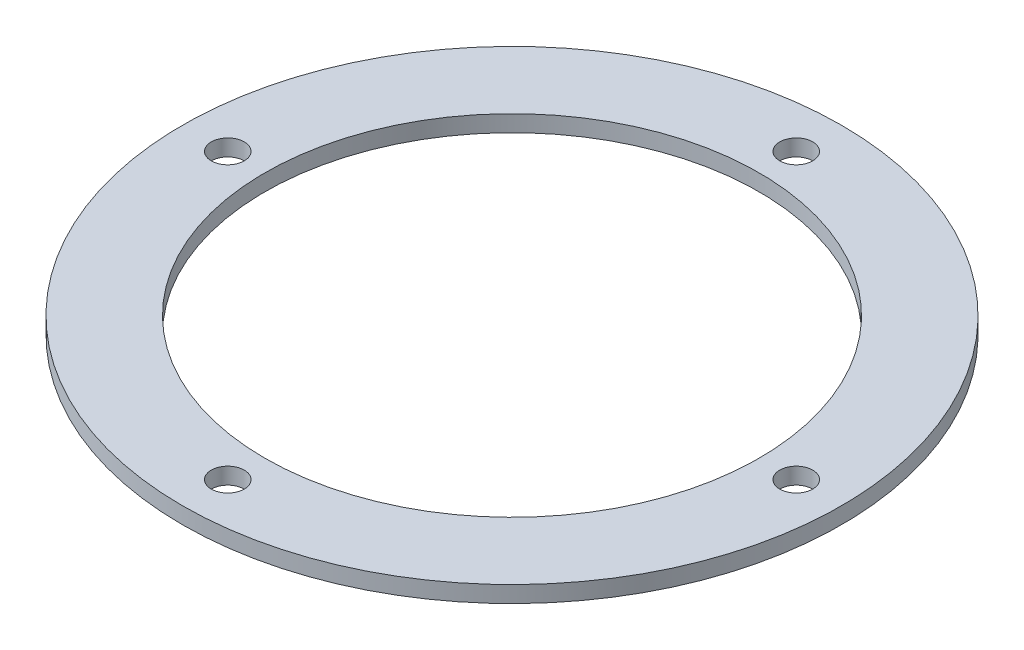
SolidWorks part; units mm, degrees
ref_plane "前视基准面" through (0, 0, 0) normal (0, 0, 1) x (1, 0, 0)
ref_plane "上视基准面" through (0, 0, 0) normal (0, 1, 0) x (1, 0, 0)
ref_plane "右视基准面" through (0, 0, 0) normal (1, 0, 0) x (0, 0, -1)
other "Configuration Table"
sketch "草图2" plane through (0, 0, 0) normal (0, 1, 0) x (1, 0, 0)
  circle A0 centre (0, 0) radius 30
  circle A1 centre (0, 0) radius 40
  circle A2 centre (0, 0) radius 34.5 construction
  circle A3 centre (0, 34.5) radius 2
  circle A4 centre (34.5, 0) radius 2
  circle A5 centre (0, -34.5) radius 2
  circle A6 centre (-34.5, 0) radius 2
  point P15 (0, 0)
  dimension "D1" = 60
  dimension "D2" = 80
  dimension "D3" = 69
  dimension "D4" = 4
  dimension "D5" = 4
extrude "凸台-拉伸1" add sketch "草图2" along normal blind 2
